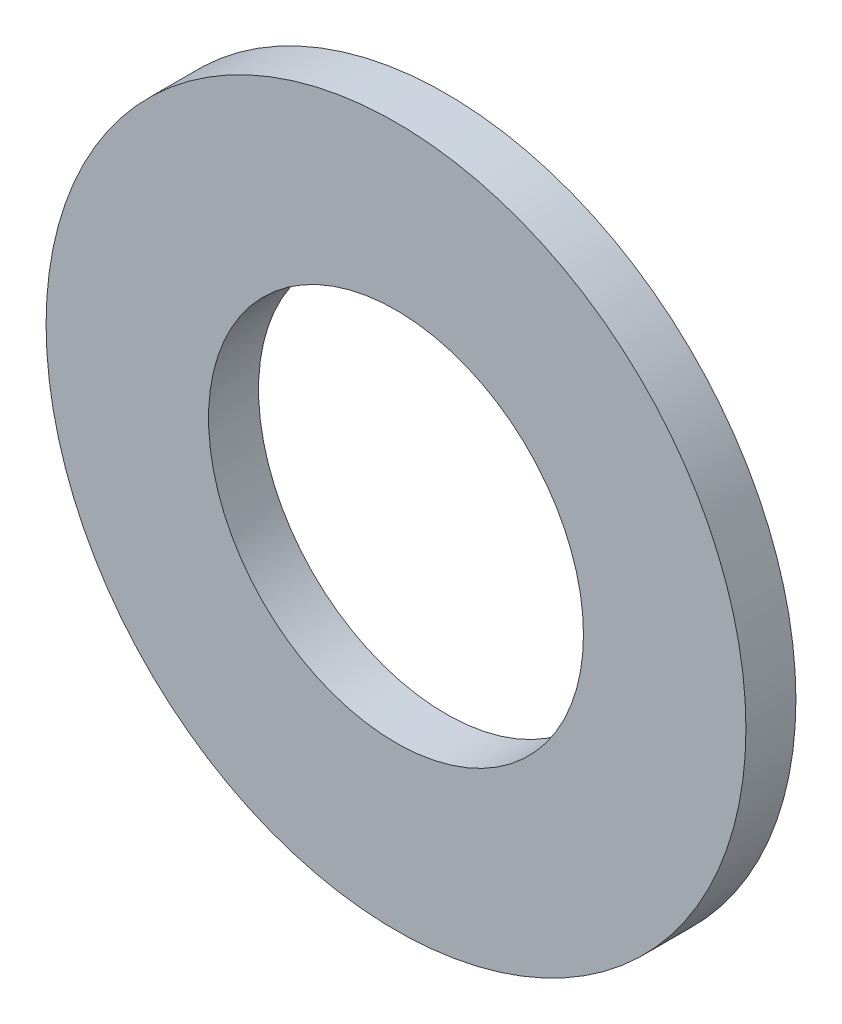
SolidWorks part; units mm, degrees
material "AISI 316 Chapa de acero inoxidable (SS)"
ref_plane "Alzado" through (0, 0, 0) normal (0, 0, 1) x (1, 0, 0)
ref_plane "Planta" through (0, 0, 0) normal (0, 1, 0) x (1, 0, 0)
ref_plane "Vista lateral" through (0, 0, 0) normal (1, 0, 0) x (0, 0, -1)
sketch "Croquis1" plane through (0, 0, 0) normal (1, 0, 0) x (0, 0, -1)
  line L0 (0, 0) -> (61.9238, 0) construction
  line L1 (0, 0) -> (0, 22.225)
  line L2 (0, 22.225) -> (3.175, 22.225)
  line L3 (3.175, 22.225) -> (3.175, 0)
  line L4 (3.175, 0) -> (0, 0)
  dimension "D1" = 3.175
  dimension "D2" = 44.45
revolve "Revolución1" add sketch "Croquis1" angle 360 about L0
sketch "Croquis2" plane through (0, 0, 0) normal (0, 0, 1) x (1, 0, 0)
  circle A0 centre (0, 0) radius 11.906
  dimension "D1" = 23.812
extrude "Cortar-Extruir1" cut sketch "Croquis2" against normal up to next
